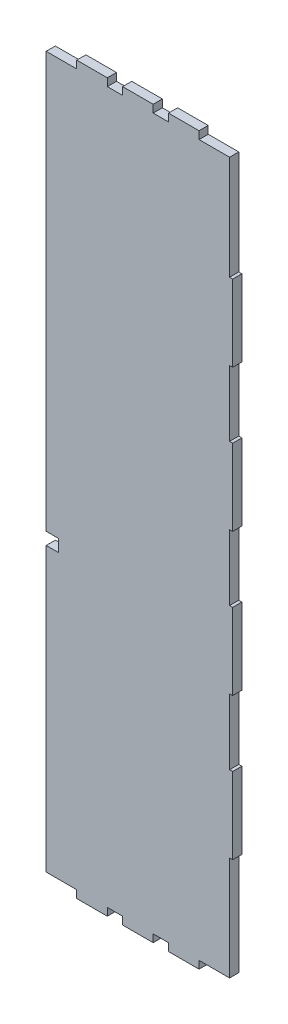
SolidWorks part; units mm, degrees
ref_plane "Front Plane" through (0, 0, 0) normal (0, 0, 1) x (1, 0, 0)
ref_plane "Top Plane" through (0, 0, 0) normal (0, 1, 0) x (1, 0, 0)
ref_plane "Right Plane" through (0, 0, 0) normal (1, 0, 0) x (0, 0, -1)
sketch "Sketch1" plane through (0, 0, 0) normal (0, 0, 1) x (1, 0, 0)
  line L1 (-60, -232.5) -> (60, -232.5)
  line L2 (-60, -232.5) -> (-60, 232.5)
  line L3 (-60, 232.5) -> (60, 232.5)
  line L4 (60, -232.5) -> (60, 232.5)
  line L5 (0, 232.5) -> (0, -232.5) construction
  line L6 (-60, 0) -> (60, 0) construction
  point P0 (0, 0)
  dimension "D1" = 465
  dimension "D2" = 120
extrude "Boss-Extrude1" add sketch "Sketch1" along normal blind 6
sketch "Sketch4" plane through (0, 0, 6) normal (0, 0, 1) x (1, 0, 0)
  line L0 (60, 232.5) -> (-60, 232.5) construction
  line L1 (-40, 237.5) -> (-20, 237.5)
  line L2 (-40, 237.5) -> (-40, 227.5)
  line L3 (-40, 227.5) -> (-20, 227.5)
  line L4 (-20, 237.5) -> (-20, 227.5)
  line L5 (-30, 227.5) -> (-30, 237.5) construction
  line L6 (-40, 232.5) -> (-20, 232.5) construction
  line L7 (-60, -232.5) -> (60, -232.5) construction
  line L8 (-10, 237.5) -> (10, 237.5)
  line L9 (-10, 237.5) -> (-10, 227.5)
  line L10 (-10, 227.5) -> (10, 227.5)
  line L11 (10, 237.5) -> (10, 227.5)
  line L12 (0, 227.5) -> (0, 237.5) construction
  line L13 (-10, 232.5) -> (10, 232.5) construction
  line L14 (40, 237.5) -> (20, 237.5)
  line L15 (40, 237.5) -> (40, 227.5)
  line L16 (40, 227.5) -> (20, 227.5)
  line L17 (20, 237.5) -> (20, 227.5)
  line L18 (30, 227.5) -> (30, 237.5) construction
  line L19 (40, 232.5) -> (20, 232.5) construction
  line L20 (-40, -227.5) -> (-20, -227.5)
  line L21 (-40, -227.5) -> (-40, -237.5)
  line L22 (-40, -237.5) -> (-20, -237.5)
  line L23 (-20, -227.5) -> (-20, -237.5)
  line L24 (-30, -237.5) -> (-30, -227.5) construction
  line L25 (-40, -232.5) -> (-20, -232.5) construction
  line L26 (60, -232.5) -> (60, 232.5) construction
  line L27 (-10, -227.5) -> (10, -227.5)
  line L28 (-10, -227.5) -> (-10, -237.5)
  line L29 (-10, -237.5) -> (10, -237.5)
  line L30 (10, -227.5) -> (10, -237.5)
  line L31 (0, -237.5) -> (0, -227.5) construction
  line L32 (-10, -232.5) -> (10, -232.5) construction
  line L33 (20, -227.5) -> (40, -227.5)
  line L34 (20, -227.5) -> (20, -237.5)
  line L35 (20, -237.5) -> (40, -237.5)
  line L36 (40, -227.5) -> (40, -237.5)
  line L37 (30, -237.5) -> (30, -227.5) construction
  line L38 (20, -232.5) -> (40, -232.5) construction
  line L39 (58, 164.5) -> (62, 164.5)
  line L40 (58, 164.5) -> (58, 114.5)
  line L41 (58, 114.5) -> (62, 114.5)
  line L42 (62, 164.5) -> (62, 114.5)
  line L43 (60, 114.5) -> (60, 164.5) construction
  line L44 (58, 139.5) -> (62, 139.5) construction
  line L46 (58, 71.5) -> (62, 71.5)
  line L47 (58, 71.5) -> (58, 21.5)
  line L48 (58, 21.5) -> (62, 21.5)
  line L49 (62, 71.5) -> (62, 21.5)
  line L50 (60, 21.5) -> (60, 71.5) construction
  line L51 (58, 46.5) -> (62, 46.5) construction
  line L52 (58, -71.5) -> (62, -71.5)
  line L53 (58, -71.5) -> (58, -21.5)
  line L54 (58, -21.5) -> (62, -21.5)
  line L55 (62, -71.5) -> (62, -21.5)
  line L56 (60, -21.5) -> (60, -71.5) construction
  line L57 (58, -46.5) -> (62, -46.5) construction
  line L58 (58, -114.5) -> (62, -114.5)
  line L59 (58, -114.5) -> (58, -164.5)
  line L60 (58, -164.5) -> (62, -164.5)
  line L61 (62, -114.5) -> (62, -164.5)
  line L62 (60, -164.5) -> (60, -114.5) construction
  line L63 (58, -139.5) -> (62, -139.5) construction
  point P0 (-30, 232.5)
  point P6 (0, 232.5)
  point P10 (30, 232.5)
  point P14 (-30, -232.5)
  point P20 (0, -232.5)
  point P24 (30, -232.5)
  point P28 (60, 139.5)
  point P34 (60, 46.5)
  point P38 (60, -46.5)
  point P42 (60, -139.5)
  dimension "D1" = 30
  dimension "D2" = 60
  dimension "D3" = 90
  dimension "D4" = 20
  dimension "D5" = 20
  dimension "D6" = 20
  dimension "D7" = 10
  dimension "D8" = 10
  dimension "D9" = 10
  dimension "D10" = 30
  dimension "D11" = 60
  dimension "D12" = 90
  dimension "D13" = 20
  dimension "D14" = 20
  dimension "D15" = 20
  dimension "D16" = 10
  dimension "D17" = 10
  dimension "D18" = 10
  dimension "D19" = 93
  dimension "D20" = 93
  dimension "D21" = 93
  dimension "D22" = 93
  dimension "D23" = 4
  dimension "D24" = 4
  dimension "D25" = 4
  dimension "D26" = 4
  dimension "D27" = 50
  dimension "D28" = 50
  dimension "D29" = 50
  dimension "D30" = 50
extrude "Boss-Extrude2" add sketch "Sketch4" against normal blind 6
sketch "Sketch5" plane through (0, 0, 6) normal (0, 0, 1) x (1, 0, 0)
  line L0 (-60, 232.5) -> (-60, -232.5) construction
  line L1 (-60, -39.4345) -> (-52, -39.4345)
  line L2 (-60, -39.4345) -> (-60, -47.4345)
  line L3 (-60, -47.4345) -> (-52, -47.4345)
  line L4 (-52, -39.4345) -> (-52, -47.4345)
  dimension "D1" = 8
  dimension "D2" = 8
extrude "Cut-Extrude1" cut sketch "Sketch5" against normal blind 10
